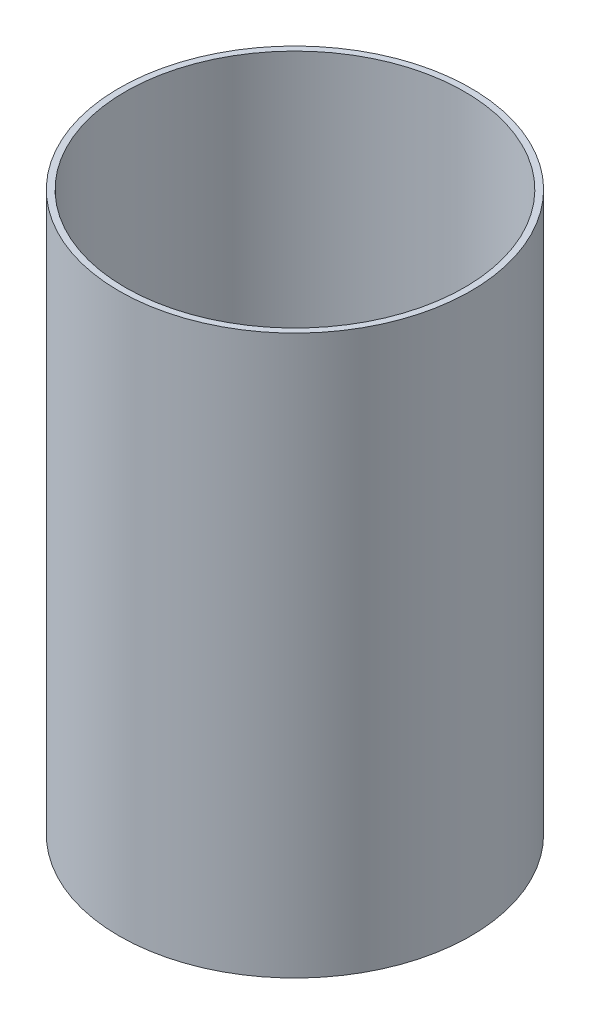
SolidWorks part; units mm, degrees
material "E-Glass Fiber"
ref_plane "Front Plane" through (0, 0, 0) normal (0, 0, 1) x (1, 0, 0)
ref_plane "Top Plane" through (0, 0, 0) normal (0, 1, 0) x (1, 0, 0)
ref_plane "Right Plane" through (0, 0, 0) normal (1, 0, 0) x (0, 0, -1)
sketch "Sketch1" plane through (0, 0, 0) normal (0, 1, 0) x (1, 0, 0)
  circle A0 centre (0, 0) radius 82
  circle A1 centre (0, 0) radius 85
  dimension "D1" = 164
  dimension "D2" = 170
extrude "Boss-Extrude1" add sketch "Sketch1" along normal blind 270
